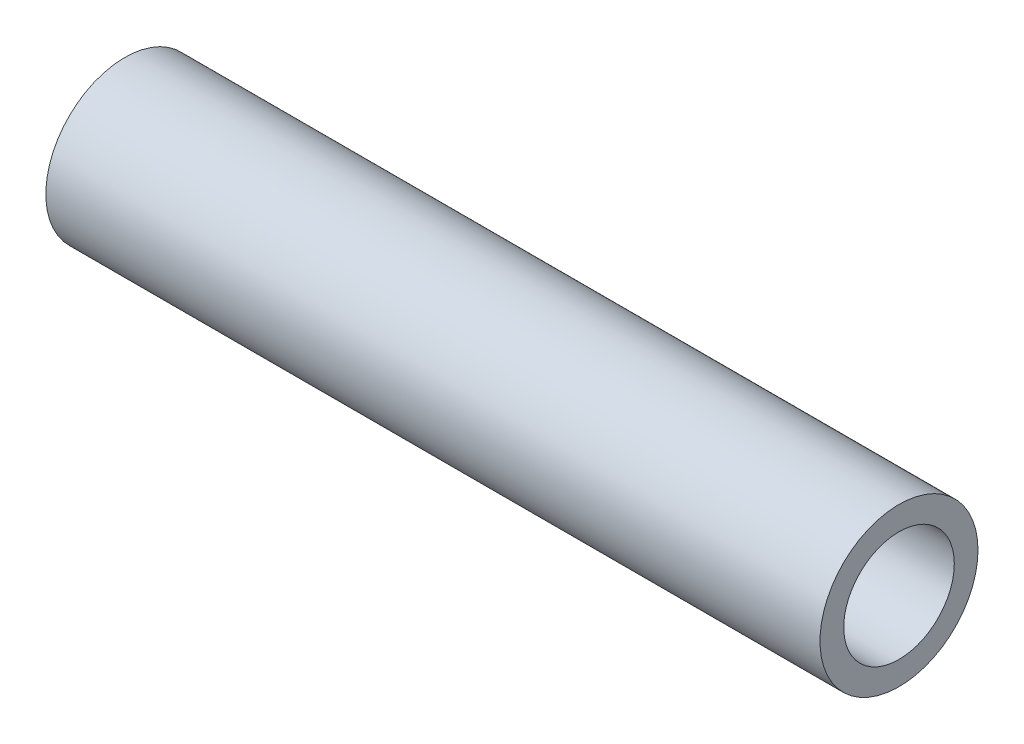
SolidWorks part; units mm, degrees
ref_plane "Front Plane" through (0, 0, 0) normal (0, 0, 1) x (1, 0, 0)
ref_plane "Top Plane" through (0, 0, 0) normal (0, 1, 0) x (1, 0, 0)
ref_plane "Right Plane" through (0, 0, 0) normal (1, 0, 0) x (0, 0, -1)
sketch "Sketch1" plane through (0, 0, 0) normal (1, 0, 0) x (0, 0, -1)
  circle A0 centre (0, 0) radius 5
  circle A1 centre (0, 0) radius 3.5
  dimension "D1" = 10
  dimension "D2" = 7
extrude "Boss-Extrude1" add sketch "Sketch1" along normal mid plane 49
sketch "Sketch2" plane through (0, 0, 0) normal (0, 0, 1) x (1, 0, 0)
  line L0 (18.5, -5) -> (18.5, 5)
  line L1 (-24.5, -5) -> (24.5, -5) construction
  line L2 (24.5, 5) -> (-24.5, 5) construction
  line L3 (24.5, -5) -> (24.5, 5) construction
  dimension "D1" = 6
